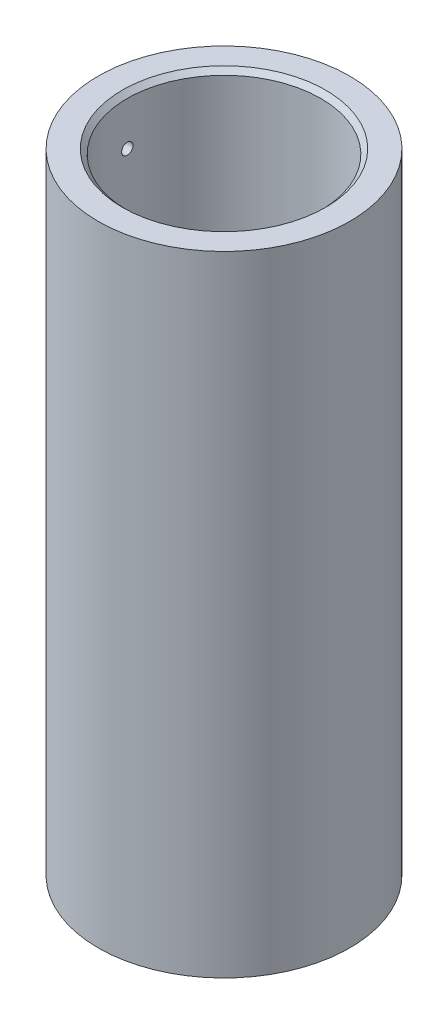
SolidWorks part; units mm, degrees
ref_plane "Front Plane" through (0, 0, 0) normal (0, 0, 1) x (1, 0, 0)
ref_plane "Top Plane" through (0, 0, 0) normal (0, 1, 0) x (1, 0, 0)
ref_plane "Right Plane" through (0, 0, 0) normal (1, 0, 0) x (0, 0, -1)
sketch "Sketch1" plane through (0, 0, 0) normal (0, 1, 0) x (1, 0, 0)
  circle A0 centre (0, 0) radius 10
  circle A1 centre (0, 0) radius 13
  dimension "D1" = 20
  dimension "D2" = 26
extrude "Boss-Extrude1" add sketch "Sketch1" along normal blind 65
chamfer "Chamfer1" distance 0.5 angle 45 2 edges at (0, 0, 10) (0, 65, 10)
sketch "Sketch5" plane through (0, 0, 0) normal (0, 0, 1) x (1, 0, 0)
  line L0 (13, 65) -> (-13, 65) construction
  line L1 (-13, 60.585) -> (-9, 60.585) construction
  line L2 (-13, 60.585) -> (-13, 59.415) construction
  line L3 (-13, 59.415) -> (-9, 59.415) construction
  line L4 (-9, 60.585) -> (-9, 59.415) construction
  line L5 (-13, 60.585) -> (-9, 59.415) construction
  line L6 (-13, 59.415) -> (-9, 60.585) construction
  line L8 (-13, 60.949) -> (-12, 60.585)
  line L9 (-12, 60.585) -> (-9, 60.585)
  line L10 (-9, 60.585) -> (-9, 60)
  line L13 (-13, 65) -> (-13, 0) construction
  line L14 (-13, 60.949) -> (-13, 60)
  line L15 (-13, 60) -> (-9, 60)
  point P0 (-11, 60)
  dimension "D1" = 1.17
  dimension "D2" = 5
  dimension "D4" = 20
  dimension "D3" = 4
  dimension "D5" = 1
revolve "Cut-Revolve4" cut sketch "Sketch5" angle 360 about L15
equation "\"pin_bore\"=14.20"
equation "\"top_outer_diameter\"=22.40"
equation "\"bottom_height\"=23.10"
equation "\"bottom_bore_height\"=11.90"
equation "\"valve_diameter\"=1.17"
equation "\"D1@Sketch5\"=\"valve_diameter\""
